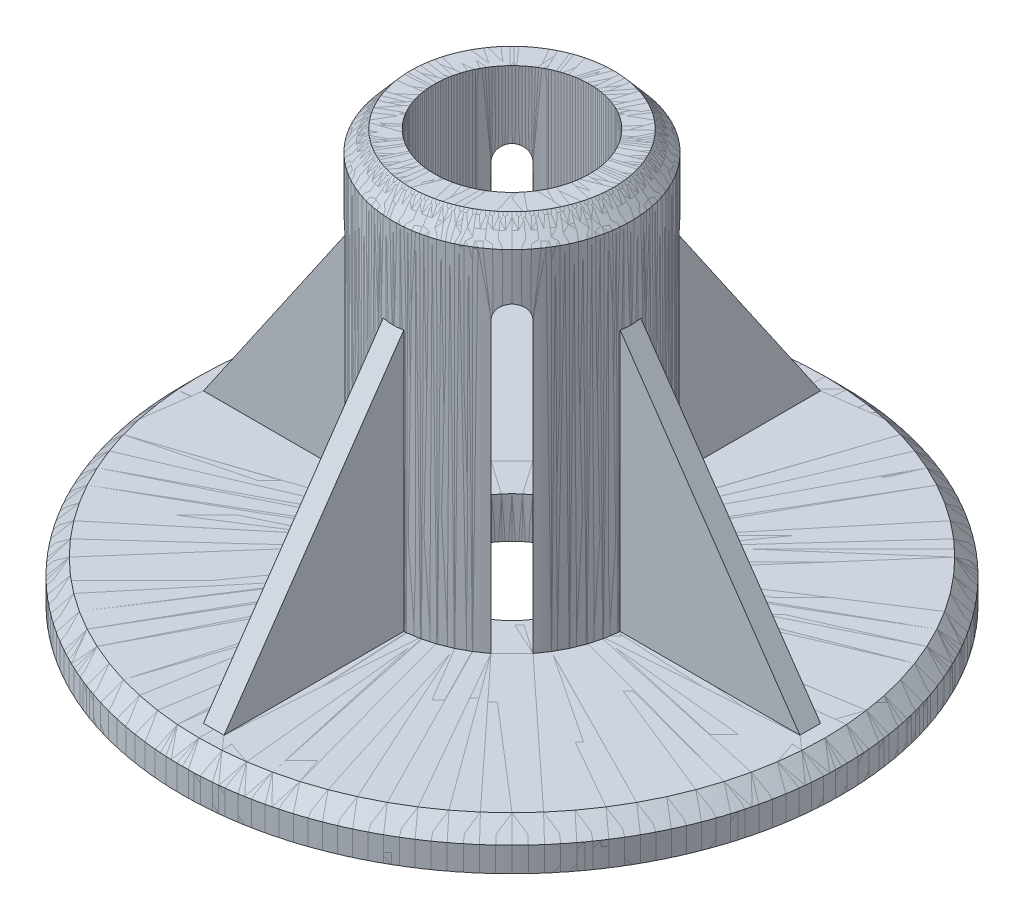
SolidWorks part; units mm, degrees
ref_plane "Front Plane" through (0, 0, 0) normal (0, 0, 1) x (1, 0, 0)
ref_plane "Top Plane" through (0, 0, 0) normal (0, 1, 0) x (1, 0, 0)
ref_plane "Right Plane" through (0, 0, 0) normal (1, 0, 0) x (0, 0, -1)
sketch "Sketch1" plane through (0, 0, 0) normal (0, 0, 1) x (1, 0, 0)
  line L0 (11.9837, 63.5) -> (15.6222, 63.5)
  line L1 (18.3337, 60.3566) -> (18.3337, 6.35)
  line L2 (18.3337, 6.35) -> (48.26, 6.35)
  line L3 (50.8, 3.81) -> (50.8, 0)
  line L4 (50.8, 0) -> (11.9837, 0)
  line L5 (11.9837, 0) -> (11.9837, 63.5)
  line L6 (47.5146, 6.35) -> (18.3337, 57.7306) construction
  line L7 (0, 0) -> (0, 55.0088) construction
  line L8 (15.6222, 63.5) -> (18.3337, 60.3566)
  line L9 (48.26, 6.35) -> (50.8, 3.81)
  dimension "D1" = 50.8
  dimension "D2" = 63.5
revolve "Revolve1" add sketch "Sketch1" angle 360 about L7
sketch "Sketch2" plane through (0, 0, 0) normal (0, 0, 1) x (1, 0, 0)
  line L0 (18.3337, 46.4862) -> (45.9677, 6.35)
  line L3 (50.8, 6.35) -> (-50.8, 6.35) construction
  line L4 (18.3337, 6.35) -> (18.3337, 60.3566) construction
rib "Rib2" sketch "Sketch2" sketch "Sketch2" thickness 3.175 extrusion direction parallel to sketch draft on no parameters "D1"=3.175
pattern_circular "CirPattern1" count 4 over 360 about axis through (0, 0, 0) along (0, 1, 0) of bodies 101
ref_plane "Plane1" through (0, 63.5, 0) normal (0, 1, 0) x (-1, 0, 0)
sketch "Sketch3" plane through (0, 63.5, 0) normal (0, 1, 0) x (-1, 0, 0)
  line L0 (0, 0) -> (12.9639, -12.9639) construction
  line L1 (0, 0) -> (50.3233, 0) construction
  line L2 (0, 0) -> (-12.9639, -12.9639) construction
  line L3 (0, 0) -> (-50.8, 0) construction
  circle A0 centre (0, 0) radius 18.3337 construction
  circle A1 centre (0, 0) radius 18.3337 construction
  circle A2 centre (0, 0) radius 50.8 construction
  circle A3 centre (0, 0) radius 50.8 construction
  dimension "D1" = 45
  dimension "D2" = 45
ref_plane "Plane2" through (-12.9639, 63.5, -12.9639) normal (-0.7071, 0, -0.7071) x (-0.7071, 0, 0.7071)
sketch "Sketch7" plane through (-12.9639, 63.5, -12.9639) normal (-0.7071, 0, -0.7071) x (-0.7071, 0, 0.7071)
  line L0 (0, -57.15) -> (0, -12.7) construction
  line L2 (50.8, -57.15) -> (-50.8, -57.15) construction
  line L5 (-2.286, -12.7) -> (-2.286, -57.15)
  line L6 (-2.286, -57.15) -> (2.286, -57.15)
  line L7 (2.286, -12.7) -> (2.286, -57.15)
  line L8 (-2.286, -12.7) -> (2.286, -57.15) construction
  line L9 (-2.286, -57.15) -> (2.286, -12.7) construction
  arc A0 (2.286, -12.7) -> (-2.286, -12.7) centre (0, -12.7) ccw
  point P5 (0, -34.925)
  point P6 (0, -34.925)
  dimension "D1" = 44.45
  dimension "D2" = 4.572
ref_plane "Plane4" through (12.9639, 63.5, -12.9639) normal (0.7071, 0, -0.7071) x (-0.7071, 0, -0.7071)
sketch "Sketch9" plane through (12.9639, 63.5, -12.9639) normal (0.7071, 0, -0.7071) x (-0.7071, 0, -0.7071)
  line L0 (0, -57.15) -> (0, -12.7) construction
  line L1 (50.8, -57.15) -> (-50.8, -57.15) construction
  line L4 (-2.032, -12.7) -> (-2.032, -57.15)
  line L5 (-2.032, -57.15) -> (2.032, -57.15)
  line L6 (2.032, -12.7) -> (2.032, -57.15)
  line L7 (-2.032, -12.7) -> (2.032, -57.15) construction
  line L8 (-2.032, -57.15) -> (2.032, -12.7) construction
  arc A0 (2.032, -12.7) -> (-2.032, -12.7) centre (0, -12.7) ccw
  point P5 (0, -34.925)
  dimension "D1" = 44.45
  dimension "D2" = 4.064
extrude "Cut-Extrude2" cut sketch "Sketch9" against normal through all
extrude "Cut-Extrude3" cut sketch "Sketch7" against normal through all
